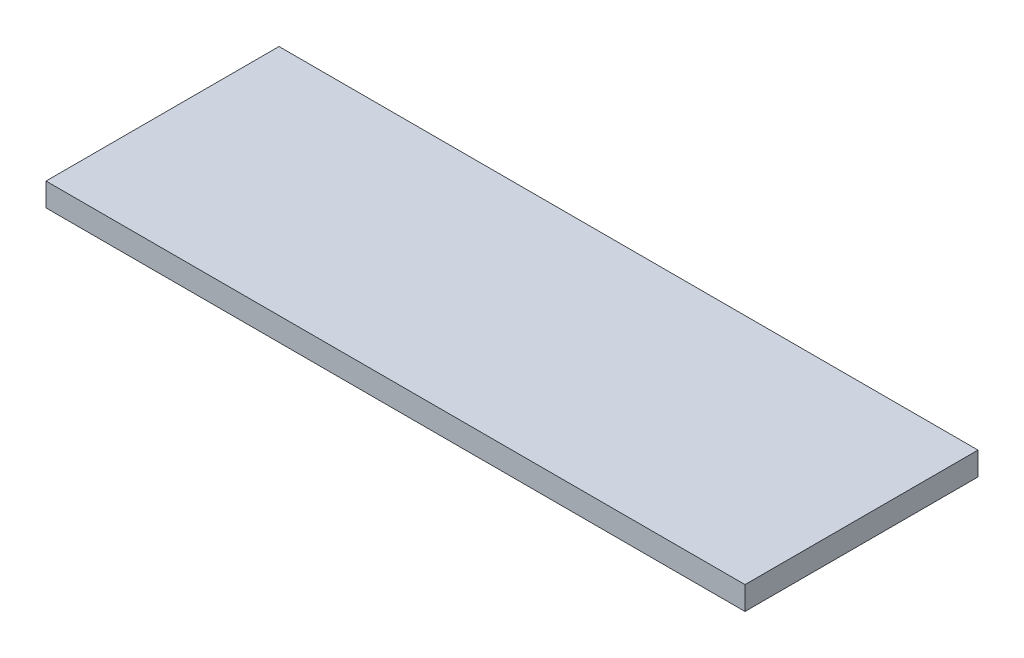
SolidWorks part; units mm, degrees
ref_plane "Front Plane" through (0, 0, 0) normal (0, 0, 1) x (1, 0, 0)
ref_plane "Top Plane" through (0, 0, 0) normal (0, 1, 0) x (1, 0, 0)
ref_plane "Right Plane" through (0, 0, 0) normal (1, 0, 0) x (0, 0, -1)
sketch "Sketch1" plane through (0, 0, 0) normal (0, 1, 0) x (1, 0, 0)
  line L1 (-75, 25) -> (75, 25)
  line L2 (-75, 25) -> (-75, -25)
  line L3 (-75, -25) -> (75, -25)
  line L4 (75, 25) -> (75, -25)
  line L5 (-75, 25) -> (75, -25) construction
  line L6 (-75, -25) -> (75, 25) construction
  point P0 (0, 0)
  dimension "D1" = 150
  dimension "D2" = 50
extrude "Boss-Extrude1" add sketch "Sketch1" along normal blind 5
